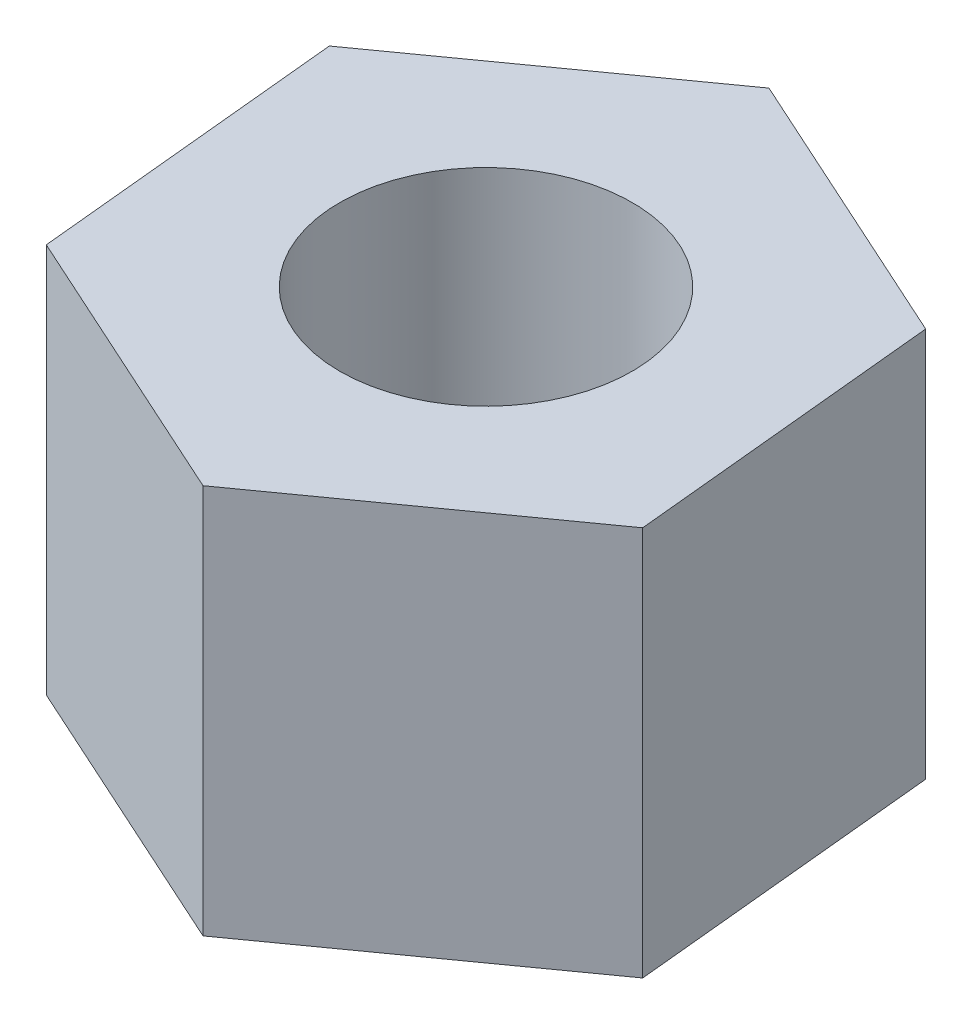
SolidWorks part; units mm, degrees
ref_plane "前视基准面" through (0, 0, 0) normal (0, 0, 1) x (1, 0, 0)
ref_plane "上视基准面" through (0, 0, 0) normal (0, 1, 0) x (1, 0, 0)
ref_plane "右视基准面" through (0, 0, 0) normal (1, 0, 0) x (0, 0, -1)
other "Configuration Table"
sketch "草图1" plane through (0, 0, 0) normal (0, 1, 0) x (1, 0, 0)
  line L1 (2.944, -1.3364) -> (2.6294, 1.8814)
  line L2 (2.6294, 1.8814) -> (-0.3146, 3.2178)
  line L3 (-0.3146, 3.2178) -> (-2.944, 1.3364)
  line L4 (-2.944, 1.3364) -> (-2.6294, -1.8814)
  line L5 (-2.6294, -1.8814) -> (0.3146, -3.2178)
  line L6 (0.3146, -3.2178) -> (2.944, -1.3364)
  circle A0 centre (0, 0) radius 2.8 construction
  circle A1 centre (0, 0) radius 1.5
extrude "凸台-拉伸1" add sketch "草图1" along normal blind 4
